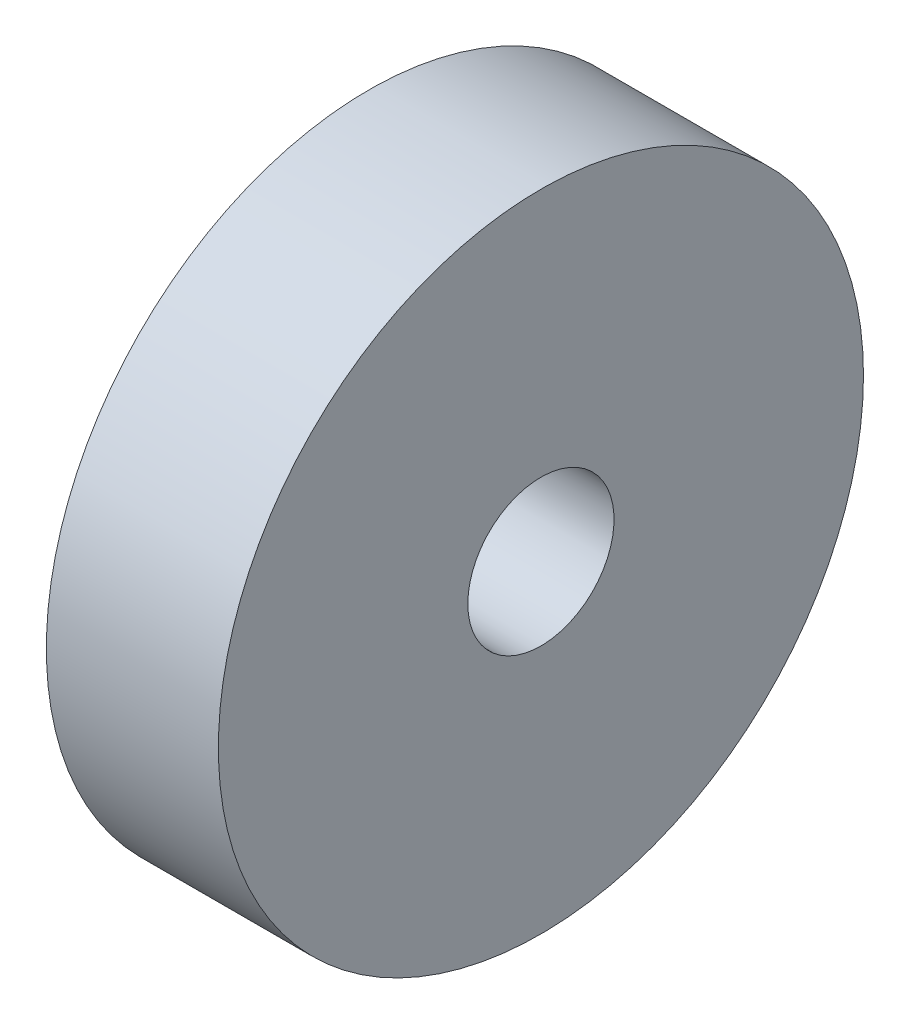
SolidWorks part; units mm, degrees
ref_plane "Front Plane" through (0, 0, 0) normal (0, 0, 1) x (1, 0, 0)
ref_plane "Top Plane" through (0, 0, 0) normal (0, 1, 0) x (1, 0, 0)
ref_plane "Right Plane" through (0, 0, 0) normal (1, 0, 0) x (0, 0, -1)
sketch "Sketch1" plane through (0, 0, 0) normal (1, 0, 0) x (0, 0, -1)
  circle A0 centre (0, 0) radius 37.5
  dimension "D1" = 75
extrude "Boss-Extrude1" add sketch "Sketch1" along normal blind 20
sketch "Sketch2" plane through (0, 0, 0) normal (-1, 0, 0) x (0, 0, 1)
  circle A0 centre (0, 0) radius 8.5
  dimension "D1" = 17
extrude "Cut-Extrude1" cut sketch "Sketch2" against normal through all
